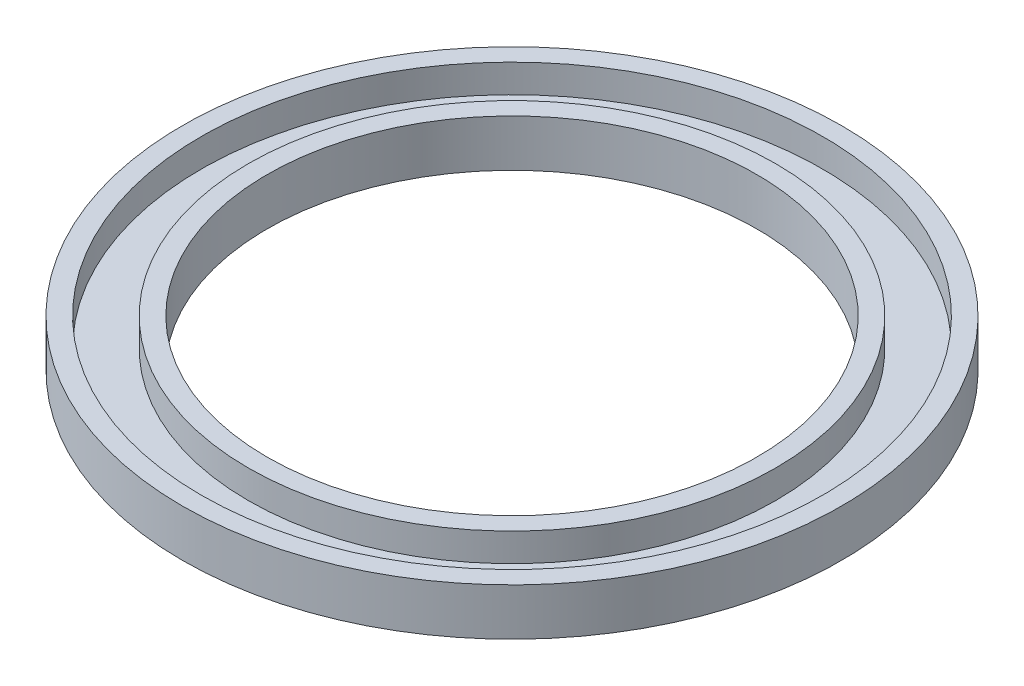
SolidWorks part; units mm, degrees
material "橡胶"
ref_plane "前视基准面" through (0, 0, 0) normal (0, 0, 1) x (1, 0, 0)
ref_plane "上视基准面" through (0, 0, 0) normal (0, 1, 0) x (1, 0, 0)
ref_plane "右视基准面" through (0, 0, 0) normal (1, 0, 0) x (0, 0, -1)
sketch "草图1" plane through (0, 0, 0) normal (0, 1, 0) x (1, 0, 0)
  circle A0 centre (0, 0) radius 17.5
  dimension "D1" = 35
extrude "凸台-拉伸1" add sketch "草图1" along normal blind 2.5
sketch "草图2" plane through (0, 2.5, 0) normal (0, 1, 0) x (1, 0, 0)
  circle A0 centre (0, 0) radius 13
  dimension "D1" = 26
extrude "切除-拉伸1" cut sketch "草图2" against normal blind 2.5
sketch "草图3" plane through (0, 2.5, 0) normal (0, 1, 0) x (1, 0, 0)
  circle A0 centre (0, 0) radius 14
  circle A1 centre (0, 0) radius 16.5
  dimension "D1" = 28
  dimension "D2" = 33
extrude "切除-拉伸2" cut sketch "草图3" against normal blind 1.5
